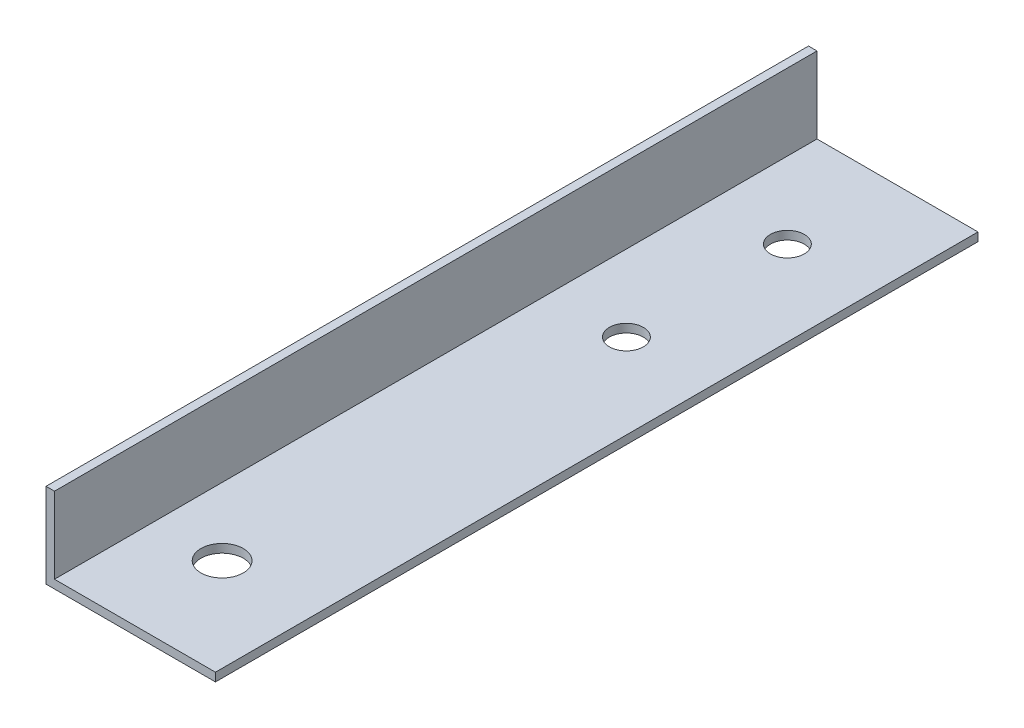
SolidWorks part; units mm, degrees
material "1060 Alloy"
ref_plane "Front Plane" through (0, 0, 0) normal (0, 0, 1) x (1, 0, 0)
ref_plane "Top Plane" through (0, 0, 0) normal (0, 1, 0) x (1, 0, 0)
ref_plane "Right Plane" through (0, 0, 0) normal (1, 0, 0) x (0, 0, -1)
sketch "Sketch1" plane through (0, 0, 0) normal (0, 0, 1) x (1, 0, 0)
  line L1 (-69.5798, 29.3277) -> (-67.5798, 29.3277)
  line L2 (-69.5798, 29.3277) -> (-69.5798, 11.3277)
  line L4 (-67.5798, 29.3277) -> (-67.5798, 11.3277)
  line L5 (-67.5798, 11.3277) -> (-29.5798, 11.3277)
  line L6 (-69.5798, 11.3277) -> (-69.5798, 9.3277)
  line L7 (-69.5798, 9.3277) -> (-29.5798, 9.3277)
  line L8 (-29.5798, 11.3277) -> (-29.5798, 9.3277)
  dimension "D1" = 20
  dimension "D2" = 40
  dimension "D3" = 2
  dimension "D4" = 2
extrude "Boss-Extrude1" add sketch "Sketch1" along normal blind 180
sketch "Sketch3" plane through (0, 9.3277, 0) normal (0, -1, 0) x (1, 0, 0)
  circle A0 centre (-49.5798, 63) radius 4
  circle A1 centre (-49.5798, 25) radius 4
  circle A2 centre (-51.5798, 156.4259) radius 5
  dimension "D1" = 10
  dimension "D2" = 0
extrude "Cut-Extrude1" cut sketch "Sketch3" against normal blind 10
